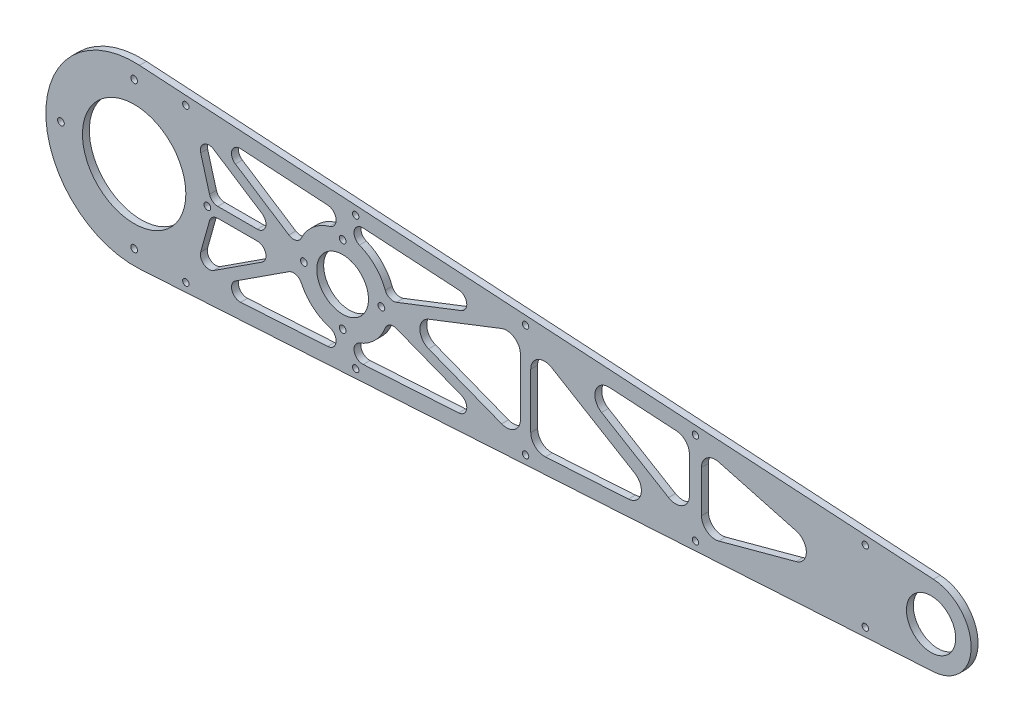
SolidWorks part; units mm, degrees
ref_plane "Front Plane" through (0, 0, 0) normal (0, 0, 1) x (1, 0, 0)
ref_plane "Top Plane" through (0, 0, 0) normal (0, 1, 0) x (1, 0, 0)
ref_plane "Right Plane" through (0, 0, 0) normal (1, 0, 0) x (0, 0, -1)
sketch "Sketch1" plane through (0, 0, 0) normal (0, 0, 1) x (1, 0, 0)
  line L0 (-231.25, 0) -> (231.25, 0) construction
  line L1 (-228.1515, 51.1562) -> (232.6579, 23.2449)
  line L2 (-228.1515, -51.1562) -> (232.6579, -23.2449)
  line L3 (191.25, 20.7438) -> (-201.25, 44.5177) construction
  circle A0 centre (231.25, 0) radius 14.2875
  arc A1 (232.6579, 23.2449) -> (232.6579, -23.2449) centre (231.25, 0) cw
  circle A2 centre (-231.25, 0) radius 42.5 construction
  circle A3 centre (-110.25, 0) radius 22.5 construction
  arc A4 (-228.1515, 51.1562) -> (-228.1515, -51.1562) centre (-231.25, 0) ccw
  circle A5 centre (-231.25, 42.5) radius 1.75 construction
  circle A6 centre (-231.25, 0) radius 30
  circle A7 centre (-110.25, 0) radius 15
  circle A8 centre (231.25, 0) radius 35.306 construction
  circle A9 centre (-201.25, 44.5177) radius 1.85
  circle A10 centre (-102.6633, 38.5462) radius 1.85
  circle A11 centre (-4.0767, 32.5748) radius 1.85
  circle A12 centre (94.51, 26.6034) radius 1.85
  circle A13 centre (193.0966, 20.632) radius 1.85
  circle A14 centre (291.6833, 14.6606) radius 1.85 construction
  circle A15 centre (193.0966, -20.632) radius 1.85
  circle A16 centre (94.51, -26.6034) radius 1.85
  circle A17 centre (-4.0767, -32.5748) radius 1.85
  circle A18 centre (-102.6633, -38.5462) radius 1.85
  circle A19 centre (-201.25, -44.5177) radius 1.85
  point P4 (0, 0)
  point P15 (-231.25, 44.25)
  point P16 (-273.75, 0)
  point P17 (-231.25, 51.25)
  point P18 (-110.25, 22.5)
  point P19 (-231.25, -42.5)
  point P20 (-188.75, 0)
  point P21 (-132.75, 0)
  point P22 (-110.25, -22.5)
  point P23 (-87.75, 0)
  dimension "D2" = 28.575
  dimension "D3" = 85
  dimension "D5" = 45
  dimension "D6" = 3.5
  dimension "D7" = 7
  dimension "D8" = 9
  dimension "D9" = 60
  dimension "D10" = 30
  dimension "D11" = 70.612
  dimension "D13" = 3.7
  dimension "D16" = 6
  dimension "D1" = 462.5
  dimension "D4" = 121
  dimension "D12" = 5
  dimension "D14" = 30
  dimension "D15" = 40
extrude "Boss-Extrude1" add sketch "Sketch1" along normal blind 4
sketch "Sketch4" plane through (0, 0, 4) normal (0, 0, 1) x (1, 0, 0)
  point P0 (-231.25, 42.5)
  point P7 (-188.75, 0)
  point P10 (-132.75, 0)
  point P13 (-110.25, 22.5)
  point P16 (-87.75, 0)
  point P19 (-110.25, -22.5)
  point P24 (-273.75, 0)
  point P28 (-231.25, -42.5)
hole_wizard "M3.5 Clearance Hole1" positions "Sketch4" profile "Sketch6" hole size "M3.5" standard "ANSI Metric" end condition up to next
sketch "Sketch6" plane through (-231.25, 42.5, 4) normal (1, 0, 0) x (0, -1, 0)
  line L0 (0, 0) -> (0, 4)
  line L1 (0, 4) -> (1.95, 4)
  line L2 (1.95, 4) -> (1.95, 0)
  line L5 (1.95, 0) -> (0, 0)
  line L11 (0, -6.35) -> (0, 107.95) construction
  dimension "Thru Hole Dia." = 3.9
  dimension "Thru Hole Depth" = 4
sketch "Sketch7" plane through (0, 0, 4) normal (0, 0, 1) x (1, 0, 0)
  line L0 (94.51, 26.6034) -> (94.51, -26.6034) construction
  line L1 (94.51, -26.6034) -> (193.0966, 0) construction
  line L2 (193.0966, 0) -> (94.51, 26.6034) construction
  line L3 (193.0966, 0) -> (-87.75, 0) construction
  line L4 (193.0966, -20.632) -> (193.0966, 20.632) construction
  line L5 (108.0942, 19.8304) -> (152.959, 7.7237)
  line L6 (152.959, -7.7237) -> (108.0942, -19.8304)
  line L7 (98.01, -12.1067) -> (98.01, 12.1067)
  line L8 (-4.0767, -32.5748) -> (-4.0767, 32.5748) construction
  line L9 (-4.0767, 32.5748) -> (94.51, -26.6034) construction
  line L10 (-4.0767, 32.5748) -> (94.51, 26.6034) construction
  line L11 (-4.0767, -32.5748) -> (94.51, -26.6034) construction
  line L12 (-87.75, 0) -> (-102.6633, 38.5462) construction
  line L13 (-102.6633, 38.5462) -> (-4.0767, 32.5748) construction
  line L14 (-4.0767, 32.5748) -> (-87.75, 0) construction
  line L15 (91.01, -5.7044) -> (91.01, 15.278)
  line L16 (83.4936, 23.2633) -> (44.6155, 25.6182)
  line L17 (40.0145, 10.7737) -> (78.8927, -12.5635)
  line L18 (11.0406, 18.8351) -> (59.2561, -10.107)
  line L19 (55.6224, -24.9515) -> (7.407, -27.8719)
  line L20 (-1.0767, -19.8865) -> (-1.0767, 11.976)
  line L21 (232.6579, 23.2449) -> (-228.1515, 51.1562) construction
  line L22 (-228.1515, -51.1562) -> (232.6579, -23.2449) construction
  line L23 (-7.0767, -16.4882) -> (-7.0767, 16.4882)
  line L24 (-17.979, 23.9432) -> (-60.3314, 7.455)
  line L25 (-60.3314, -7.455) -> (-17.979, -23.9432)
  line L27 (-79.0235, 6.6167) -> (-41.3873, 21.2687)
  line L28 (-42.899, 30.919) -> (-98.3486, 34.2776)
  line L32 (-132.75, 0) -> (-188.75, 0) construction
  line L33 (-188.75, 0) -> (-201.25, 44.5177) construction
  line L34 (-201.25, 44.5177) -> (-132.75, 0) construction
  line L35 (-132.75, 0) -> (-102.6633, 38.5462) construction
  line L36 (-102.6633, 38.5462) -> (-201.25, 44.5177) construction
  line L37 (-172.4851, 29.4014) -> (-141.466, 9.2423)
  line L39 (-118.8811, 35.5212) -> (-169.4581, 38.5847)
  line L40 (-192.6227, 24.8897) -> (-187.5008, 6.6483)
  line L41 (-182.6869, 3) -> (-159.7406, 3)
  line L42 (-157.016, 12.1924) -> (-185.0842, 30.4338)
  line L44 (-118.8811, -35.5212) -> (-169.4581, -38.5847)
  line L45 (-172.4851, -29.4014) -> (-141.466, -9.2423)
  line L46 (-157.016, -12.1924) -> (-185.0842, -30.4338)
  line L47 (-192.6227, -24.8897) -> (-187.5008, -6.6483)
  line L48 (-182.6869, -3) -> (-159.7406, -3)
  line L50 (-42.899, -30.919) -> (-98.3486, -34.2776)
  line L51 (-79.0235, -6.6167) -> (-41.3873, -21.2687)
  arc A0 (152.959, 7.7237) -> (152.959, -7.7237) centre (150.8748, 0) cw
  arc A1 (108.0942, -19.8304) -> (98.01, -12.1067) centre (106.01, -12.1067) cw
  arc A2 (108.0942, 19.8304) -> (98.01, 12.1067) centre (106.01, 12.1067) ccw
  arc A3 (91.01, 15.278) -> (83.4936, 23.2633) centre (83.01, 15.278) ccw
  arc A4 (44.6155, 25.6182) -> (40.0145, 10.7737) centre (44.1318, 17.6328) ccw
  arc A5 (91.01, -5.7044) -> (78.8927, -12.5635) centre (83.01, -5.7044) cw
  arc A6 (59.2561, -10.107) -> (55.6224, -24.9515) centre (55.1388, -16.9661) cw
  arc A7 (7.407, -27.8719) -> (-1.0767, -19.8865) centre (6.9233, -19.8865) cw
  arc A8 (11.0406, 18.8351) -> (-1.0767, 11.976) centre (6.9233, 11.976) ccw
  arc A9 (-7.0767, -16.4882) -> (-17.979, -23.9432) centre (-15.0767, -16.4882) cw
  arc A10 (-7.0767, 16.4882) -> (-17.979, 23.9432) centre (-15.0767, 16.4882) ccw
  arc A11 (-60.3314, 7.455) -> (-60.3314, -7.455) centre (-57.4292, 0) ccw
  arc A12 (-41.3873, 21.2687) -> (-42.899, 30.919) centre (-43.2013, 25.9281) ccw
  arc A18 (-172.4851, 29.4014) -> (-169.4581, 38.5847) centre (-169.7604, 33.5938) cw
  arc A21 (-159.7406, 3) -> (-157.016, 12.1924) centre (-159.7406, 8) ccw
  arc A22 (-187.5008, 6.6483) -> (-182.6869, 3) centre (-182.6869, 8) ccw
  arc A23 (-192.6227, 24.8897) -> (-185.0842, 30.4338) centre (-187.8089, 26.2413) cw
  arc A26 (-172.4851, -29.4014) -> (-169.4581, -38.5847) centre (-169.7604, -33.5938) ccw
  arc A27 (-192.6227, -24.8897) -> (-185.0842, -30.4338) centre (-187.8089, -26.2413) ccw
  arc A28 (-187.5008, -6.6483) -> (-182.6869, -3) centre (-182.6869, -8) cw
  arc A29 (-159.7406, -3) -> (-157.016, -12.1924) centre (-159.7406, -8) cw
  circle A30 centre (-110.25, 0) radius 15 construction
  circle A31 centre (-110.25, 0) radius 15 construction
  circle A32 centre (-110.25, 0) radius 22.5 construction
  arc A33 (-98.3486, 34.2776) -> (-100.492, 24.638) centre (-98.6509, 29.2867) ccw
  arc A34 (-85.5061, 9.4862) -> (-100.492, 24.638) centre (-110.25, 0) ccw
  arc A37 (-85.5061, 9.4862) -> (-79.0235, 6.6167) centre (-80.8374, 11.276) ccw
  arc A38 (-41.3873, -21.2687) -> (-42.899, -30.919) centre (-43.2013, -25.9281) cw
  arc A39 (-98.3486, -34.2776) -> (-100.492, -24.638) centre (-98.6509, -29.2867) cw
  arc A40 (-134.2189, 11.3023) -> (-117.7355, 25.4208) centre (-110.25, 0) cw
  arc A41 (-85.5061, -9.4862) -> (-100.492, -24.638) centre (-110.25, 0) cw
  arc A42 (-85.5061, -9.4862) -> (-79.0235, -6.6167) centre (-80.8374, -11.276) cw
  arc A43 (-118.8811, 35.5212) -> (-117.7355, 25.4208) centre (-119.1931, 30.3707) cw
  arc A44 (-134.2189, 11.3023) -> (-141.466, 9.2423) centre (-138.7414, 13.4348) cw
  arc A45 (-118.8811, -35.5212) -> (-117.7355, -25.4208) centre (-119.1931, -30.3707) ccw
  arc A46 (-134.2189, -11.3023) -> (-117.7355, -25.4208) centre (-110.25, 0) ccw
  arc A47 (-134.2189, -11.3023) -> (-141.466, -9.2423) centre (-138.7414, -13.4348) ccw
  point P36 (181.5816, 0)
  point P59 (-79.4807, 0)
  dimension "D8" = 8
  dimension "D11" = 5
  dimension "D12" = 8
  dimension "D18" = 5
  dimension "D19" = 5
  dimension "D10" = 4
  dimension "D21" = 5
  dimension "D1" = 3
  dimension "D2" = 7
  dimension "D3" = 8
  dimension "D4" = 8
  dimension "D5" = 8
  dimension "D6" = 6
  dimension "D7" = 6
  dimension "D9" = 8
  dimension "D13" = 8
  dimension "D15" = 6
  dimension "D16" = 3
  dimension "D17" = 6
extrude "Cut-Extrude1" cut sketch "Sketch7" against normal blind 10
